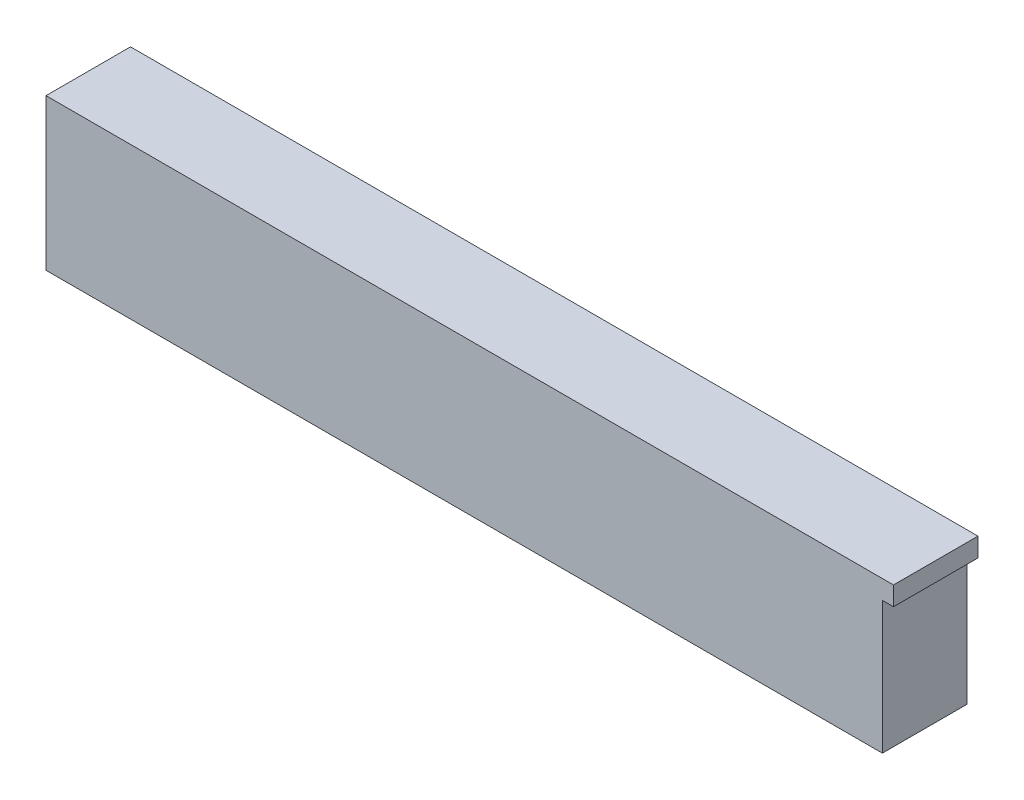
SolidWorks part; units mm, degrees
ref_plane "Front Plane" through (0, 0, 0) normal (0, 0, 1) x (1, 0, 0)
ref_plane "Top Plane" through (0, 0, 0) normal (0, 1, 0) x (1, 0, 0)
ref_plane "Right Plane" through (0, 0, 0) normal (1, 0, 0) x (0, 0, -1)
sketch "Sketch1" plane through (0, 0, 0) normal (0, 0, 1) x (1, 0, 0)
  line L1 (0, 0) -> (376, 0)
  line L2 (0, 0) -> (0, 68)
  line L3 (0, 68) -> (376, 68)
  line L4 (376, 0) -> (376, 68)
  dimension "D1" = 376
  dimension "D2" = 68
extrude "Boss-Extrude1" add sketch "Sketch1" along normal blind 38
sketch "Sketch2" plane through (376, 0, 0) normal (1, 0, 0) x (0, 0, -1)
  line L0 (-38, 0) -> (-38, 68) construction
  line L1 (0, 68) -> (-38, 68)
  line L2 (0, 68) -> (0, 59.5)
  line L3 (0, 59.5) -> (-38, 59.5)
  line L4 (-38, 68) -> (-38, 59.5)
  dimension "D1" = 8.5
extrude "Boss-Extrude2" add sketch "Sketch2" along normal blind 5
